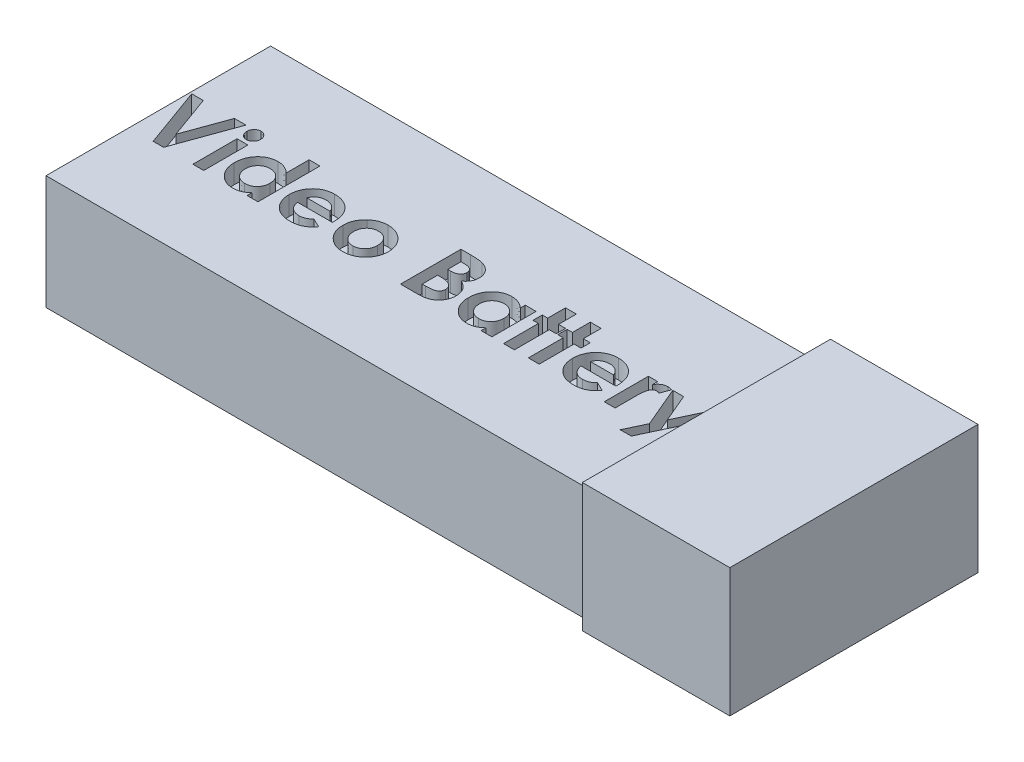
SolidWorks part; units mm, degrees
ref_plane "Front Plane" through (0, 0, 0) normal (0, 0, 1) x (1, 0, 0)
ref_plane "Top Plane" through (0, 0, 0) normal (0, 1, 0) x (1, 0, 0)
ref_plane "Right Plane" through (0, 0, 0) normal (1, 0, 0) x (0, 0, -1)
sketch "Sketch1" plane through (0, 0, 0) normal (0, 1, 0) x (1, 0, 0)
  line L1 (-28.8, 11.8) -> (0, 11.8)
  line L2 (-28.8, 11.8) -> (-28.8, 0)
  line L3 (-28.8, 0) -> (0, 0)
  line L4 (0, 11.8) -> (0, 0)
  dimension "D1" = 28.8
  dimension "D2" = 11.8
extrude "Boss-Extrude1" add sketch "Sketch1" along normal blind 6
ref_plane "Plane1" through (0, 0, 0) normal (1, 0, 0) x (0, 0, -1)
sketch "Sketch3" plane through (0, 0, 0) normal (1, 0, 0) x (0, 0, -1)
  line L0 (0, 6) -> (0, 0) construction
  line L1 (-0.62, 6.75) -> (12.42, 6.75)
  line L2 (-0.62, 6.75) -> (-0.62, 0)
  line L3 (-0.62, 0) -> (12.42, 0)
  line L4 (12.42, 6.75) -> (12.42, 0)
  line L5 (0, 0) -> (11.8, 0) construction
  line L6 (11.8, 6) -> (11.8, 0) construction
  dimension "D2" = 6.75
  dimension "D3" = 0
  dimension "D4" = 0.62
  dimension "D5" = 0.62
extrude "Boss-Extrude2" add sketch "Sketch3" along normal blind 7.75
ref_plane "Plane2" through (0, 6, 0) normal (0, 1, 0) x (1, 0, 0)
sketch "Sketch4" plane through (0, 6, 0) normal (0, 1, 0) x (1, 0, 0)
  line L0 (-28.8, 11.8) -> (-28.8, 0) construction
  text T0 "<b>Video Battery</b>"
extrude "Cut-Extrude1" cut sketch "Sketch4" against normal blind 1
